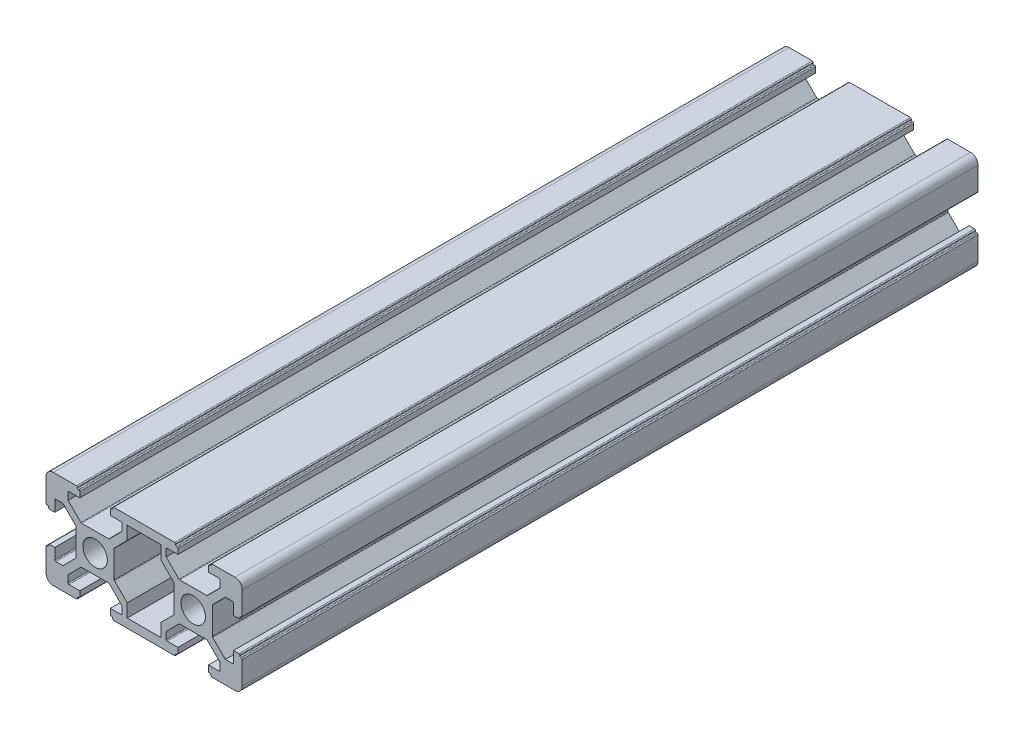
SolidWorks part; units mm, degrees
ref_plane "前视基准面" through (0, 0, 0) normal (0, 0, 1) x (1, 0, 0)
ref_plane "上视基准面" through (0, 0, 0) normal (0, 1, 0) x (1, 0, 0)
ref_plane "右视基准面" through (0, 0, 0) normal (1, 0, 0) x (0, 0, -1)
sketch "Sketch1" plane through (0, 0, 0) normal (0, 0, 1) x (1, 0, 0)
  line L0 (-8.5, 10) -> (-3.8, 10)
  line L3 (-8.5, -10) -> (-3.8, -10)
  line L5 (-10, 8.5) -> (-10, 3.8)
  line L6 (-2.7565, 3.9) -> (2.7565, 3.9)
  line L9 (-2.7565, -3.9) -> (2.7565, -3.9)
  line L10 (3.9, 2.7565) -> (3.9, -2.7565)
  line L11 (-3.9, 2.7565) -> (-3.9, -2.7565)
  line L12 (-3.9586, -2.8979) -> (-6.5607, -5.5)
  line L13 (3.6, 9.7) -> (3.6, 9.8)
  line L14 (3.1, -8.2) -> (5.3, -8.2)
  line L15 (-2.8979, -3.9586) -> (-5.5, -6.5607)
  line L16 (-3.1, -8.2) -> (-3.1, -9.3)
  line L17 (3.1, -8.2) -> (3.1, -9.3)
  line L18 (-5.5, -6.5607) -> (-5.5, -8)
  line L19 (5.5, -6.5607) -> (5.5, -8)
  line L20 (-5.3, -8.2) -> (-3.1, -8.2)
  line L21 (-3.4, -9.5) -> (-3.3, -9.5)
  line L22 (3.8, -10) -> (8.5, -10)
  line L23 (3.3, -9.5) -> (3.4, -9.5)
  line L24 (-3.6, -9.7) -> (-3.6, -9.8)
  line L25 (3.6, -9.7) -> (3.6, -9.8)
  line L26 (-6.5607, -5.5) -> (-8, -5.5)
  line L27 (-9.7, -3.6) -> (-9.8, -3.6)
  line L28 (-9.5, -3.4) -> (-9.5, -3.3)
  line L29 (-8.2, -3.1) -> (-9.3, -3.1)
  line L30 (-8.2, -5.3) -> (-8.2, -3.1)
  line L31 (-10, -3.8) -> (-10, -8.5)
  line L33 (3.8, 10) -> (8.5, 10)
  line L34 (2.8979, -3.9586) -> (5.5, -6.5607)
  line L40 (3.9586, -2.8979) -> (6.5607, -5.5)
  line L41 (3.3, 9.5) -> (3.4, 9.5)
  line L42 (30, 8.5) -> (30, 3.8)
  line L43 (3.1, 8.2) -> (3.1, 9.3)
  line L44 (3.1, 8.2) -> (5.3, 8.2)
  line L45 (5.5, 6.5607) -> (5.5, 8)
  line L46 (2.8979, 3.9586) -> (5.5, 6.5607)
  line L52 (3.9586, 2.8979) -> (6.5607, 5.5)
  line L53 (-3.6, 9.7) -> (-3.6, 9.8)
  line L54 (-3.4, 9.5) -> (-3.3, 9.5)
  line L55 (-3.1, 8.2) -> (-3.1, 9.3)
  line L56 (-5.3, 8.2) -> (-3.1, 8.2)
  line L57 (-5.5, 6.5607) -> (-5.5, 8)
  line L58 (-2.8979, 3.9586) -> (-5.5, 6.5607)
  line L59 (-9.5, 3.4) -> (-9.5, 3.3)
  line L60 (-9.7, 3.6) -> (-9.8, 3.6)
  line L61 (-8.2, 3.1) -> (-9.3, 3.1)
  line L62 (-8.2, 5.3) -> (-8.2, 3.1)
  line L63 (-6.5607, 5.5) -> (-8, 5.5)
  line L64 (-3.9586, 2.8979) -> (-6.5607, 5.5)
  line L65 (29.7, 3.6) -> (29.8, 3.6)
  line L66 (29.5, 3.4) -> (29.5, 3.3)
  line L67 (28.2, 3.1) -> (29.3, 3.1)
  line L68 (28.2, 5.3) -> (28.2, 3.1)
  line L69 (26.5607, 5.5) -> (28, 5.5)
  line L70 (23.9586, 2.8979) -> (26.5607, 5.5)
  line L71 (23.9, 2.7565) -> (23.9, -2.7565)
  line L72 (23.9586, -2.8979) -> (26.5607, -5.5)
  line L73 (26.5607, -5.5) -> (28, -5.5)
  line L74 (28.2, -5.3) -> (28.2, -3.1)
  line L75 (28.2, -3.1) -> (29.3, -3.1)
  line L76 (29.5, -3.4) -> (29.5, -3.3)
  line L77 (29.7, -3.6) -> (29.8, -3.6)
  line L78 (30, -3.8) -> (30, -8.5)
  line L79 (28.5, -10) -> (23.8, -10)
  line L80 (23.6, -9.7) -> (23.6, -9.8)
  line L81 (23.4, -9.5) -> (23.3, -9.5)
  line L82 (23.1, -8.2) -> (23.1, -9.3)
  line L83 (25.3, -8.2) -> (23.1, -8.2)
  line L84 (25.5, -6.5607) -> (25.5, -8)
  line L85 (22.8979, -3.9586) -> (25.5, -6.5607)
  line L86 (22.7565, -3.9) -> (17.2435, -3.9)
  line L87 (17.1021, -3.9586) -> (14.5, -6.5607)
  line L88 (14.5, -6.5607) -> (14.5, -8)
  line L89 (16.9, -8.2) -> (14.7, -8.2)
  line L90 (16.9, -8.2) -> (16.9, -9.3)
  line L91 (16.7, -9.5) -> (16.6, -9.5)
  line L92 (16.4, -9.7) -> (16.4, -9.8)
  line L93 (16.2, -10) -> (11.5, -10)
  line L94 (13.4393, 5.5) -> (13.4393, 8.2)
  line L96 (6.5607, 5.5) -> (6.5607, 8.2)
  line L97 (6.5607, 8.2) -> (13.4393, 8.2)
  line L99 (16.0414, -2.8979) -> (13.4393, -5.5)
  line L100 (16.1, 2.7565) -> (16.1, -2.7565)
  line L101 (16.0414, 2.8979) -> (13.4393, 5.5)
  line L107 (16.2, 10) -> (11.5, 10)
  line L108 (16.4, 9.7) -> (16.4, 9.8)
  line L109 (16.7, 9.5) -> (16.6, 9.5)
  line L110 (16.9, 8.2) -> (16.9, 9.3)
  line L111 (16.9, 8.2) -> (14.7, 8.2)
  line L112 (14.5, 6.5607) -> (14.5, 8)
  line L113 (17.1021, 3.9586) -> (14.5, 6.5607)
  line L114 (22.7565, 3.9) -> (17.2435, 3.9)
  line L115 (22.8979, 3.9586) -> (25.5, 6.5607)
  line L116 (25.5, 6.5607) -> (25.5, 8)
  line L117 (25.3, 8.2) -> (23.1, 8.2)
  line L118 (23.1, 8.2) -> (23.1, 9.3)
  line L119 (23.4, 9.5) -> (23.3, 9.5)
  line L120 (23.6, 9.7) -> (23.6, 9.8)
  line L121 (28.5, 10) -> (23.8, 10)
  line L122 (13.4393, -5.5) -> (13.4393, -8.2)
  line L124 (6.5607, -5.5) -> (6.5607, -8.2)
  line L125 (6.5607, -8.2) -> (13.4393, -8.2)
  line L127 (8.5, 10) -> (11.5, 10)
  line L128 (8.5, -10) -> (11.5, -10)
  arc A3 (-8.5, -10) -> (-10, -8.5) centre (-8.5, -8.5) cw
  arc A4 (-10, 8.5) -> (-8.5, 10) centre (-8.5, 8.5) cw
  arc A5 (3.4, -9.5) -> (3.6, -9.7) centre (3.4, -9.7) cw
  arc A6 (3.8, -10) -> (3.6, -9.8) centre (3.8, -9.8) cw
  arc A7 (3.3, -9.5) -> (3.1, -9.3) centre (3.3, -9.3) cw
  arc A8 (5.3, -8.2) -> (5.5, -8) centre (5.3, -8) ccw
  arc A9 (-3.9, -2.7565) -> (-3.9586, -2.8979) centre (-4.1, -2.7565) cw
  arc A10 (-3.9, 2.7565) -> (-3.9586, 2.8979) centre (-4.1, 2.7565) ccw
  arc A11 (-2.7565, 3.9) -> (-2.8979, 3.9586) centre (-2.7565, 4.1) cw
  arc A12 (2.7565, 3.9) -> (2.8979, 3.9586) centre (2.7565, 4.1) ccw
  arc A13 (3.9586, 2.8979) -> (3.9, 2.7565) centre (4.1, 2.7565) ccw
  arc A14 (3.9, -2.7565) -> (3.9586, -2.8979) centre (4.1, -2.7565) ccw
  arc A15 (-2.8979, -3.9586) -> (-2.7565, -3.9) centre (-2.7565, -4.1) cw
  arc A16 (2.7565, -3.9) -> (2.8979, -3.9586) centre (2.7565, -4.1) cw
  arc A17 (-3.6, -9.8) -> (-3.8, -10) centre (-3.8, -9.8) cw
  arc A18 (-3.3, -9.5) -> (-3.1, -9.3) centre (-3.3, -9.3) ccw
  arc A19 (-3.6, -9.7) -> (-3.4, -9.5) centre (-3.4, -9.7) cw
  arc A20 (-8.2, 5.3) -> (-8, 5.5) centre (-8, 5.3) cw
  arc A23 (-8.2, -5.3) -> (-8, -5.5) centre (-8, -5.3) ccw
  arc A24 (-5.3, -8.2) -> (-5.5, -8) centre (-5.3, -8) cw
  arc A31 (3.1, 9.3) -> (3.3, 9.5) centre (3.3, 9.3) cw
  arc A32 (3.6, 9.8) -> (3.8, 10) centre (3.8, 9.8) cw
  arc A33 (3.6, 9.7) -> (3.4, 9.5) centre (3.4, 9.7) cw
  arc A34 (-3.8, 10) -> (-3.6, 9.8) centre (-3.8, 9.8) cw
  arc A35 (-3.3, 9.5) -> (-3.1, 9.3) centre (-3.3, 9.3) cw
  arc A36 (-3.4, 9.5) -> (-3.6, 9.7) centre (-3.4, 9.7) cw
  arc A37 (5.5, 8) -> (5.3, 8.2) centre (5.3, 8) ccw
  arc A38 (-5.5, 8) -> (-5.3, 8.2) centre (-5.3, 8) cw
  arc A39 (-10, 3.8) -> (-9.8, 3.6) centre (-9.8, 3.8) ccw
  arc A40 (-9.5, 3.3) -> (-9.3, 3.1) centre (-9.3, 3.3) ccw
  arc A41 (-9.7, 3.6) -> (-9.5, 3.4) centre (-9.7, 3.4) cw
  arc A42 (-10, -3.8) -> (-9.8, -3.6) centre (-9.8, -3.8) cw
  arc A43 (-9.5, -3.3) -> (-9.3, -3.1) centre (-9.3, -3.3) cw
  arc A44 (-9.5, -3.4) -> (-9.7, -3.6) centre (-9.7, -3.4) cw
  arc A45 (30, 8.5) -> (28.5, 10) centre (28.5, 8.5) ccw
  arc A46 (30, 3.8) -> (29.8, 3.6) centre (29.8, 3.8) cw
  arc A47 (29.7, 3.6) -> (29.5, 3.4) centre (29.7, 3.4) ccw
  arc A48 (29.5, 3.3) -> (29.3, 3.1) centre (29.3, 3.3) cw
  arc A49 (28.2, 5.3) -> (28, 5.5) centre (28, 5.3) ccw
  arc A50 (23.9, 2.7565) -> (23.9586, 2.8979) centre (24.1, 2.7565) cw
  arc A51 (23.9, -2.7565) -> (23.9586, -2.8979) centre (24.1, -2.7565) ccw
  arc A52 (28.2, -5.3) -> (28, -5.5) centre (28, -5.3) cw
  arc A53 (29.5, -3.3) -> (29.3, -3.1) centre (29.3, -3.3) ccw
  arc A54 (29.5, -3.4) -> (29.7, -3.6) centre (29.7, -3.4) ccw
  arc A55 (30, -3.8) -> (29.8, -3.6) centre (29.8, -3.8) ccw
  arc A56 (28.5, -10) -> (30, -8.5) centre (28.5, -8.5) ccw
  arc A57 (23.6, -9.8) -> (23.8, -10) centre (23.8, -9.8) ccw
  arc A58 (23.6, -9.7) -> (23.4, -9.5) centre (23.4, -9.7) ccw
  arc A59 (23.3, -9.5) -> (23.1, -9.3) centre (23.3, -9.3) cw
  arc A60 (25.3, -8.2) -> (25.5, -8) centre (25.3, -8) ccw
  arc A61 (22.8979, -3.9586) -> (22.7565, -3.9) centre (22.7565, -4.1) ccw
  arc A62 (17.2435, -3.9) -> (17.1021, -3.9586) centre (17.2435, -4.1) ccw
  arc A63 (14.7, -8.2) -> (14.5, -8) centre (14.7, -8) cw
  arc A64 (16.7, -9.5) -> (16.9, -9.3) centre (16.7, -9.3) ccw
  arc A65 (16.6, -9.5) -> (16.4, -9.7) centre (16.6, -9.7) ccw
  arc A66 (16.2, -10) -> (16.4, -9.8) centre (16.2, -9.8) ccw
  arc A72 (16.1, -2.7565) -> (16.0414, -2.8979) centre (15.9, -2.7565) cw
  arc A73 (16.0414, 2.8979) -> (16.1, 2.7565) centre (15.9, 2.7565) cw
  arc A79 (16.4, 9.8) -> (16.2, 10) centre (16.2, 9.8) ccw
  arc A80 (16.4, 9.7) -> (16.6, 9.5) centre (16.6, 9.7) ccw
  arc A81 (16.9, 9.3) -> (16.7, 9.5) centre (16.7, 9.3) ccw
  arc A82 (14.5, 8) -> (14.7, 8.2) centre (14.7, 8) cw
  arc A83 (17.2435, 3.9) -> (17.1021, 3.9586) centre (17.2435, 4.1) cw
  arc A84 (22.7565, 3.9) -> (22.8979, 3.9586) centre (22.7565, 4.1) ccw
  arc A85 (25.5, 8) -> (25.3, 8.2) centre (25.3, 8) ccw
  arc A86 (23.3, 9.5) -> (23.1, 9.3) centre (23.3, 9.3) ccw
  arc A87 (23.4, 9.5) -> (23.6, 9.7) centre (23.4, 9.7) ccw
  arc A88 (23.8, 10) -> (23.6, 9.8) centre (23.8, 9.8) ccw
  point P11 (3.9, 3.9)
  point P19 (3.3697, 4.4303)
  point P20 (-10.6428, -10.6428)
  point P25 (-11.1731, -10.1124)
  point P26 (4.4303, 3.3697)
  point P28 (-10.1124, -11.1731)
  dimension "D3" = 0.2
  dimension "D4" = 0.2
  dimension "D5" = 0.2
  dimension "D8" = 0.2
  dimension "D9" = 0.2
  dimension "D10" = 0.2
  dimension "D6" = 1.8
  dimension "D7" = 0.5
extrude "Boss-Extrude1" add sketch "Sketch1" along normal blind 150
ref_plane "hole" through (0, 0, 150) normal (0, 0, 1) x (1, 0, 0)
sketch "Sketch2" plane through (0, 0, 150) normal (0, 0, 1) x (1, 0, 0)
  circle A0 centre (0, 0) radius 2.5
  circle A1 centre (20, 0) radius 2.5
  dimension "D1" = 5
extrude "Cut-Extrude1" cut sketch "Sketch2" against normal through all
